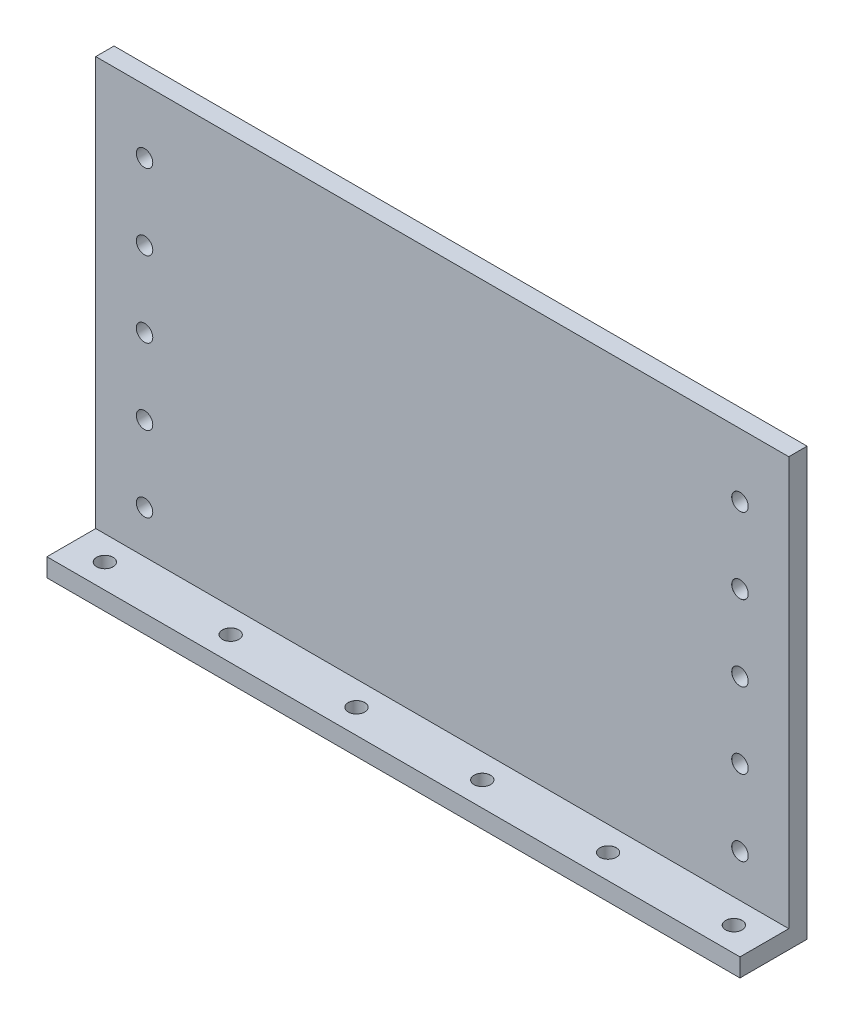
SolidWorks part; units mm, degrees
ref_plane "Front Plane" through (0, 0, 0) normal (0, 0, 1) x (1, 0, 0)
ref_plane "Top Plane" through (0, 0, 0) normal (0, 1, 0) x (1, 0, 0)
ref_plane "Right Plane" through (0, 0, 0) normal (1, 0, 0) x (0, 0, -1)
sketch "Sketch1" plane through (0, 0, 0) normal (0, 0, 1) x (1, 0, 0)
  line L1 (284, -175) -> (-284, -175)
  line L2 (284, -175) -> (284, 175)
  line L3 (284, 175) -> (-284, 175)
  line L4 (-284, -175) -> (-284, 175)
  line L5 (284, -175) -> (-284, 175) construction
  line L6 (284, 175) -> (-284, -175) construction
  point P0 (0, 0)
  dimension "D1" = 568
  dimension "D2" = 350
extrude "Boss-Extrude1" add sketch "Sketch1" along normal blind 15
sketch "Sketch2" plane through (0, 0, 15) normal (0, 0, 1) x (1, 0, 0)
  line L0 (0, 221.1142) -> (0, -209.4605) construction
sketch "Sketch4" plane through (0, 0, 15) normal (0, 0, 1) x (1, 0, 0)
  line L0 (-284, -160) -> (284, -160)
  line L1 (-284, 175) -> (-284, -175) construction
  line L2 (284, -175) -> (284, 175) construction
  line L3 (-284, -175) -> (284, -175) construction
  line L4 (-284, -175) -> (284, -175)
  line L5 (-284, -175) -> (-284, -160)
  line L6 (284, -175) -> (284, -160)
  dimension "D1" = 15
extrude "Boss-Extrude3" add sketch "Sketch4" along normal blind 40
sketch "Sketch9" plane through (0, 0, 15) normal (0, 0, 1) x (1, 0, 0)
  line L0 (284, -160) -> (284, 175) construction
  line L1 (284, 175) -> (-284, 175) construction
  point P0 (244, 123)
  dimension "D1" = 40
  dimension "D2" = 52
hole_wizard "M12 Clearance Hole2" positions "Sketch9" profile "Sketch10" hole size "M12" standard "ANSI Metric" end condition through all
sketch "Sketch10" plane through (244, 123, 15) normal (1, 0, 0) x (0, -1, 0)
  line L0 (0, 0) -> (0, 15)
  line L1 (0, 15) -> (6.75, 15)
  line L2 (6.75, 15) -> (6.75, 0.021)
  line L3 (6.75, 0.021) -> (6.775, 0)
  line L5 (6.775, 0) -> (0, 0)
  line L6 (-6.75, 0.021) -> (-6.775, 0) construction
  line L11 (0, -6.35) -> (0, 107.95) construction
  dimension "Thru Hole Dia." = 13.5
  dimension "Thru Hole Depth" = 15
  dimension "Near C'Sink Dia." = 13.55
  dimension "Near C'Sink Angle" = 100
pattern_linear "LPattern1" count 5 spacing 62 along (0, -1, 0) of "M12 Clearance Hole2"
sketch "Sketch13" plane through (0, 0, 0) normal (0, 0, 1) x (1, 0, 0)
  line L0 (284, 175) -> (-284, 175) construction
  line L1 (-284, 175) -> (-284, -160) construction
  point P0 (-244, 123)
  dimension "D1" = 52
  dimension "D2" = 40
hole_wizard "M12 Clearance Hole3" positions "Sketch13" profile "Sketch14" hole size "M12" standard "ANSI Metric" end condition through all
sketch "Sketch14" plane through (-244, 123, 0) normal (1, 0, 0) x (0, 1, 0)
  line L0 (0, 0) -> (0, 55)
  line L1 (0, 55) -> (6.75, 55)
  line L2 (6.75, 55) -> (6.75, 0.021)
  line L3 (6.75, 0.021) -> (6.775, 0)
  line L5 (6.775, 0) -> (0, 0)
  line L6 (-6.75, 0.021) -> (-6.775, 0) construction
  line L11 (0, -6.35) -> (0, 107.95) construction
  dimension "Thru Hole Dia." = 13.5
  dimension "Thru Hole Depth" = 55
  dimension "Near C'Sink Dia." = 13.55
  dimension "Near C'Sink Angle" = 100
pattern_linear "LPattern2" count 5 spacing 62 along (0, -1, 0) of "M12 Clearance Hole3"
sketch "Sketch15" plane through (0, -160, 0) normal (0, 1, 0) x (1, 0, 0)
  line L0 (284, -55) -> (284, -15) construction
  line L1 (284, -55) -> (-284, -55) construction
  point P0 (259, -35)
  dimension "D1" = 25
  dimension "D2" = 20
hole_wizard "M12 Clearance Hole4" positions "Sketch15" profile "Sketch16" hole size "M12" standard "ANSI Metric" end condition through all
sketch "Sketch16" plane through (259, -160, 35) normal (1, 0, 0) x (0, 0, 1)
  line L0 (0, 0) -> (0, 15)
  line L1 (0, 15) -> (6.75, 15)
  line L2 (6.75, 15) -> (6.75, 0.021)
  line L3 (6.75, 0.021) -> (6.775, 0)
  line L5 (6.775, 0) -> (0, 0)
  line L6 (-6.75, 0.021) -> (-6.775, 0) construction
  line L11 (0, -6.35) -> (0, 107.95) construction
  dimension "Thru Hole Dia." = 13.5
  dimension "Thru Hole Depth" = 15
  dimension "Near C'Sink Dia." = 13.55
  dimension "Near C'Sink Angle" = 100
pattern_linear "LPattern3" count 6 spacing 103.1 along (-1, 0, 0) of "M12 Clearance Hole4"
